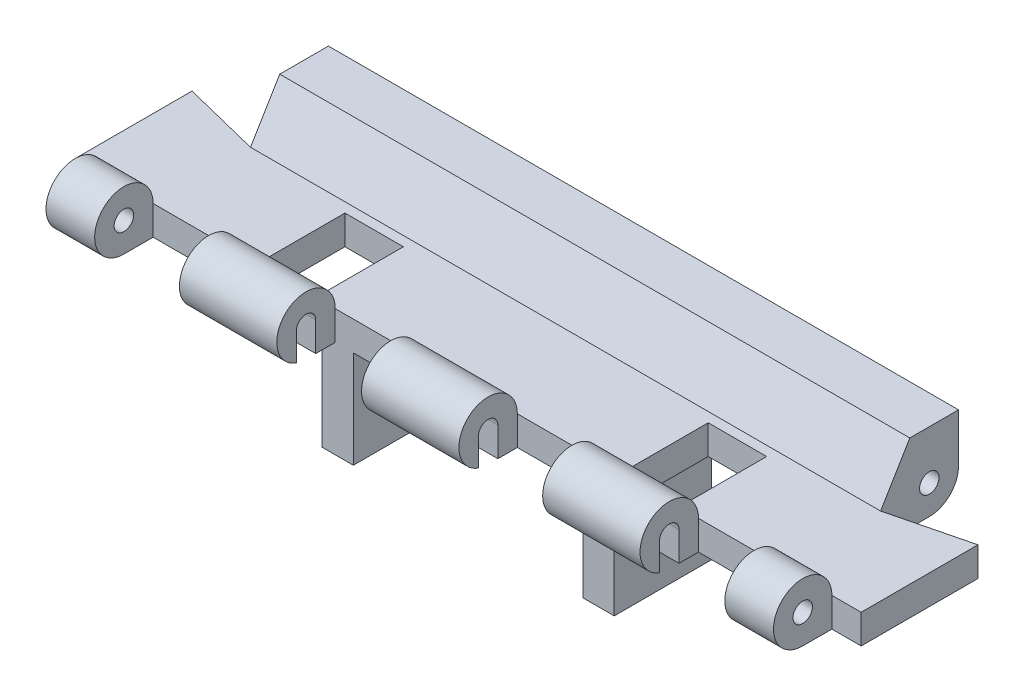
SolidWorks part; units mm, degrees
material "ABS PC"
ref_plane "Front Plane" through (0, 0, 0) normal (0, 0, 1) x (1, 0, 0)
ref_plane "Top Plane" through (0, 0, 0) normal (0, 1, 0) x (1, 0, 0)
ref_plane "Right Plane" through (0, 0, 0) normal (1, 0, 0) x (0, 0, -1)
sketch "Sketch3" plane through (0, 0, 0) normal (1, 0, 0) x (0, 0, -1)
  line L0 (-9, -1.5) -> (-7.5, -1.5)
  line L1 (-7.5, 0) -> (-2.5, 0)
  line L2 (1.5, 0) -> (1.5, 2.5)
  line L3 (1.5, 2.5) -> (-1, 2.5)
  line L4 (-1, 2.5) -> (-2.5, 0)
  line L5 (-2.5, -1.5) -> (0, -1.5)
  line L7 (-7.5, -1.5) -> (-7.5, -6.5)
  line L8 (-7.5, -6.5) -> (-2.5, -6.5)
  line L9 (-2.5, -1.5) -> (-2.5, -6.5)
  circle A0 centre (0, 0) radius 0.5
  circle A1 centre (-9, 0) radius 0.5
  arc A2 (-7.5, 0) -> (-9, -1.5) centre (-9, 0) ccw
  arc A3 (0, -1.5) -> (1.5, 0) centre (0, 0) ccw
  circle A4 centre (-9, 0) radius 1.5 construction
  circle A5 centre (0, 0) radius 1.5 construction
  dimension "D1" = 1
  dimension "D2" = 1
  dimension "D3" = 9
  dimension "D5" = 5
  dimension "D7" = 2.5
  dimension "D8" = 2.5
  dimension "D9" = 5
  dimension "D4" = 1
  dimension "D6" = 1
extrude "Boss-Extrude2" add sketch "Sketch3" along normal blind 40.35
sketch "Sketch4" plane through (0, 0, 7.5) normal (0, 0, 1) x (1, 0, 0)
  line L0 (40.35, -6.5) -> (0, -6.5) construction
  line L1 (12.68, -6.5) -> (14.28, -6.5)
  line L2 (12.68, -6.5) -> (12.68, -1.5)
  line L3 (12.68, -1.5) -> (14.28, -1.5)
  line L4 (14.28, -6.5) -> (14.28, -1.5)
  line L5 (40.35, -1.5) -> (0, -1.5) construction
  line L6 (0, -1.5) -> (0, -6.5) construction
  line L7 (26.075, -6.5) -> (27.675, -6.5)
  line L8 (26.075, -6.5) -> (26.075, -1.5)
  line L9 (26.075, -1.5) -> (27.675, -1.5)
  line L10 (27.675, -6.5) -> (27.675, -1.5)
  line L11 (40.35, -1.5) -> (40.35, -6.5) construction
  line L13 (0, -6.5) -> (12.68, -6.5)
  line L14 (0, -6.5) -> (0, -1.5)
  line L15 (0, -1.5) -> (12.68, -1.5)
  line L16 (12.68, -6.5) -> (12.68, -1.5)
  line L17 (40.35, -6.5) -> (27.675, -6.5)
  line L18 (40.35, -6.5) -> (40.35, -1.5)
  line L19 (40.35, -1.5) -> (27.675, -1.5)
  line L20 (27.675, -6.5) -> (27.675, -1.5)
  line L21 (26.075, -6.5) -> (14.28, -6.5)
  line L22 (26.075, -6.5) -> (26.075, -1.5)
  line L23 (26.075, -1.5) -> (14.28, -1.5)
  line L24 (14.28, -6.5) -> (14.28, -1.5)
  line M5 (0, -1.5) -> (0, -6.5)
  line M6 (0, -6.5) -> (40.35, -6.5)
  line M7 (40.35, -6.5) -> (40.35, -1.5)
  line M8 (40.35, -1.5) -> (0, -1.5)
  dimension "D1" = 12.68
  dimension "D2" = 12.675
  dimension "D3" = 1.6
  dimension "D4" = 1.6
extrude "Cut-Extrude1" cut sketch "Sketch4" against normal blind 40.35 contours L2 M6 M8 M5 | L8 L4 M6 M8 | L10 M6 M7 M8
sketch "Sketch5" plane through (0, 0, 0) normal (0, 1, 0) x (1, 0, 0)
  line L0 (0, -10.5) -> (40.35, -10.5) construction
  line L1 (0, -7.5) -> (1.5, -7.5)
  line L2 (0, -7.5) -> (0, -10.5)
  line L3 (0, -10.5) -> (1.5, -10.5)
  line L4 (1.5, -7.5) -> (1.5, -10.5)
  line L5 (40.35, -7.5) -> (0, -7.5) construction
  line L6 (4, -10.5) -> (8.35, -10.5)
  line L7 (4, -10.5) -> (4, -7.5)
  line L8 (4, -7.5) -> (8.35, -7.5)
  line L9 (8.35, -10.5) -> (8.35, -7.5)
  line L11 (13.35, -7.5) -> (17.7, -7.5)
  line L12 (13.35, -7.5) -> (13.35, -10.5)
  line L13 (13.35, -10.5) -> (17.7, -10.5)
  line L14 (17.7, -7.5) -> (17.7, -10.5)
  line L15 (40.35, -10.5) -> (38.85, -10.5)
  line L16 (40.35, -10.5) -> (40.35, -7.5)
  line L17 (40.35, -7.5) -> (38.85, -7.5)
  line L18 (38.85, -10.5) -> (38.85, -7.5)
  line L19 (36.35, -10.5) -> (32, -10.5)
  line L20 (36.35, -10.5) -> (36.35, -7.5)
  line L21 (36.35, -7.5) -> (32, -7.5)
  line L22 (32, -10.5) -> (32, -7.5)
  line L23 (27, -10.5) -> (22.7, -10.5)
  line L24 (27, -10.5) -> (27, -7.5)
  line L25 (27, -7.5) -> (22.7, -7.5)
  line L26 (22.7, -10.5) -> (22.7, -7.5)
  dimension "D1" = 1.5
  dimension "D2" = 1.5
  dimension "D3" = 2.5
  dimension "D4" = 2.5
  dimension "D5" = 4.35
  dimension "D6" = 4.35
  dimension "D7" = 5
  dimension "D8" = 4.35
  dimension "D9" = 5
  dimension "D10" = 5
extrude "Cut-Extrude2" cut sketch "Sketch5" against normal through all both and the other way through all
sketch "Sketch6" plane through (4, 0, 0) normal (1, 0, 0) x (0, 0, -1)
  line L0 (-9.5, 0) -> (-9.5, -1.4142)
  line L1 (-8.5, 0) -> (-8.5, -1.8627)
  line L2 (-8.5, -1.8627) -> (-9.5, -1.8627)
  line L3 (-9.5, -1.8627) -> (-9.5, -1.4142)
  arc A0 (-8.5, 0) -> (-9.5, 0) centre (-9, 0) ccw
  arc A1 (-7.5, 0) -> (-9, -1.5) centre (-9, 0) ccw construction
extrude "Cut-Extrude3" cut sketch "Sketch6" along normal up to surface (32.35 mm away) up to face at (36.35, 0, 8.5)
sketch "Sketch7" plane through (0, 0, 0) normal (0, 1, 0) x (1, 0, 0)
  line L6 (27, -7.5) -> (32, -7.5)
  line L18 (28, -3) -> (31, -3)
  line L20 (28, -7) -> (31, -7)
  line L22 (9.35, -3) -> (12.35, -3)
  line L24 (9.35, -7) -> (12.35, -7)
  line L25 (9.35, -6.5) -> (9.35, -3.5)
  line L27 (12.35, -6.5) -> (12.35, -3.5)
  line L29 (28, -6.5) -> (28, -3.5)
  line L31 (31, -6.5) -> (31, -3.5)
  line L33 (9.35, -3.5) -> (9.35, -3)
  line L34 (12.35, -3.5) -> (12.35, -3)
  line L35 (9.35, -6.5) -> (9.35, -7)
  line L36 (28, -3.5) -> (28, -3)
  line L37 (31, -3.5) -> (31, -3)
  line L38 (12.35, -6.5) -> (12.35, -7)
  line L39 (8.85, -7) -> (12.85, -7) construction
  line L40 (28, -6.5) -> (28, -7)
  line L41 (31, -6.5) -> (31, -7)
  line L42 (12.85, -7) -> (12.85, -3) construction
  line L43 (8.85, -3) -> (12.85, -3) construction
  line L44 (8.85, -7) -> (8.85, -3) construction
  line L45 (9.35, -6.5) -> (12.35, -6.5) construction
  line L46 (9.35, -3.5) -> (12.35, -3.5) construction
  line L47 (27.5, -3) -> (31.5, -3) construction
  line L48 (27, -2.5) -> (32, -2.5) construction
  line L49 (27, -7.5) -> (27, -2.5) construction
  line L50 (27.5, -7) -> (27.5, -3) construction
  line L51 (27.5, -7) -> (31.5, -7) construction
  line L52 (28, -3.5) -> (31, -3.5) construction
  line L53 (28, -6.5) -> (31, -6.5) construction
  line L54 (31.5, -7) -> (31.5, -3) construction
  line L55 (32, -7.5) -> (32, -2.5) construction
  dimension "D1" = 0.5
  dimension "D2" = 0.5
sketch "Sketch9" plane through (0, -1.5, 0) normal (0, -1, 0) x (1, 0, 0)
  line L0 (0, -1.5) -> (0, 1.5)
  line L1 (0, 7.5) -> (0, 0) construction
  line L2 (0, 1.5) -> (4, 2.5)
  line L3 (4, 2.5) -> (4, -1.5)
  line L4 (40.35, -1.5) -> (0, -1.5) construction
  line L5 (4, -1.5) -> (0, -1.5)
  line L6 (40.35, -1.5) -> (36.35, -1.5)
  line L7 (36.35, -1.5) -> (36.35, 2.5)
  line L8 (36.35, 2.5) -> (40.35, 1.5)
  line L9 (40.35, 7.5) -> (40.35, 0) construction
  line L10 (40.35, 1.5) -> (40.35, -1.5)
  dimension "D1" = 3
  dimension "D2" = 4
  dimension "D3" = 4
  dimension "D4" = 3
  dimension "D5" = 4
  dimension "D6" = 4
extrude "Cut-Extrude5" cut sketch "Sketch9" against normal through all both and the other way through all
sketch "Sketch10" plane through (0, 0, 0) normal (0, 1, 0) x (1, 0, 0)
  line L1 (4, -2.5) -> (-2.5183, -2.5)
  line L2 (4, -2.5) -> (4, 0)
  line L3 (4, 0) -> (-2.5183, 0)
  line L4 (-2.5183, -2.5) -> (-2.5183, 0)
  line L5 (36.35, -2.5) -> (41.0516, -2.5)
  line L6 (36.35, -2.5) -> (36.35, -0.2264)
  line L7 (36.35, -0.2264) -> (41.0516, -0.2264)
  line L8 (41.0516, -2.5) -> (41.0516, -0.2264)
extrude "Cut-Extrude6" cut sketch "Sketch10" along normal up to surface (2.5 mm away) up to face at (20.175, 2.5, -0.25)
sketch "Sketch12" plane through (0, -1.5, 0) normal (0, -1, 0) x (1, 0, 0)
  line L0 (36.35, -1.5) -> (4, -1.5) construction
  line L1 (8.35, -1.5) -> (13.35, -1.5)
  line L2 (8.35, -1.5) -> (8.35, 1.5)
  line L3 (8.35, 1.5) -> (13.35, 1.5)
  line L4 (13.35, -1.5) -> (13.35, 1.5)
  line L6 (17.7, -1.5) -> (22.7, -1.5)
  line L7 (17.7, -1.5) -> (17.7, 1.5)
  line L8 (17.7, 1.5) -> (22.7, 1.5)
  line L9 (22.7, -1.5) -> (22.7, 1.5)
  line L10 (32, -1.5) -> (27, -1.5)
  line L11 (32, -1.5) -> (32, 1.5)
  line L12 (32, 1.5) -> (27, 1.5)
  line L13 (27, -1.5) -> (27, 1.5)
  dimension "D1" = 3
  dimension "D2" = 3
  dimension "D3" = 3
extrude "Cut-Extrude7" cut sketch "Sketch12" against normal blind 3
extrude "Cut-Extrude8" cut sketch "Sketch7" against normal blind 3 contours L38 L27 L34 L22 L33 L25 L35 L24 | L41 L31 L37 L18 L36 L29 L40 L20
fillet "Fillet1" radius 1 3 edges at (29.5, 1.5, 1.5) (20.2, 1.5, 1.5) (10.85, 1.5, 1.5)
ref_plane "Plane1" through (20.175, 0, 0) normal (-1, 0, 0) x (0, 0, 1)
